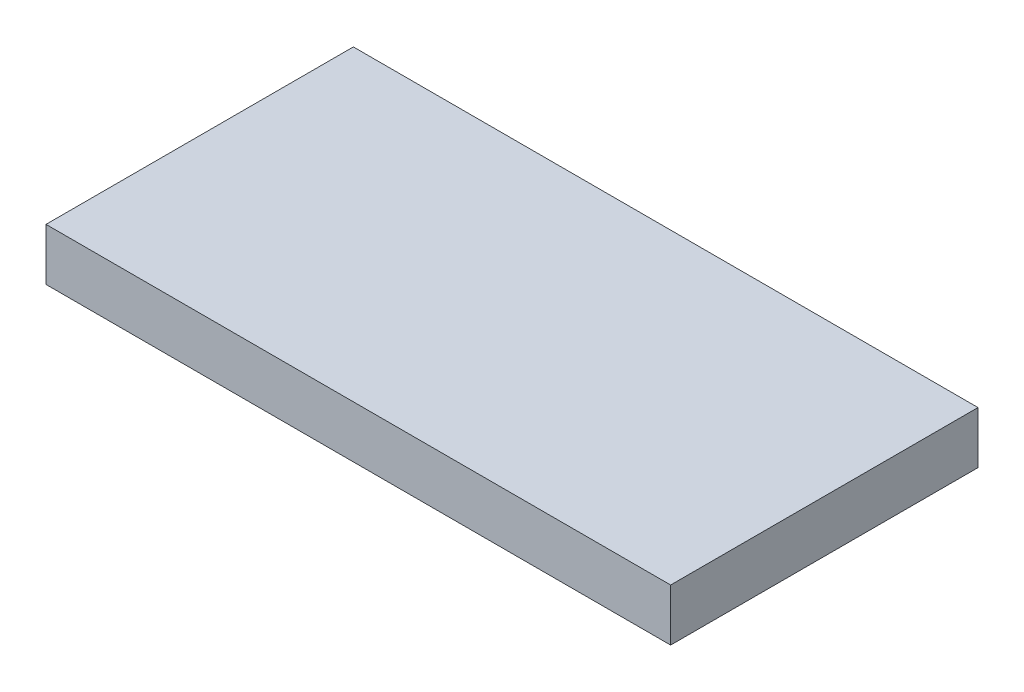
SolidWorks part; units mm, degrees
ref_plane "Front Plane" through (0, 0, 0) normal (0, 0, 1) x (1, 0, 0)
ref_plane "Top Plane" through (0, 0, 0) normal (0, 1, 0) x (1, 0, 0)
ref_plane "Right Plane" through (0, 0, 0) normal (1, 0, 0) x (0, 0, -1)
sketch "Sketch1" plane through (0, 0, 0) normal (0, 0, 1) x (1, 0, 0)
  line L0 (39, 84.25) -> (102, 84.25)
  line L1 (102, 84.25) -> (102, 89.5)
  line L2 (102, 89.5) -> (39, 89.5)
  line L3 (39, 89.5) -> (39, 84.25)
extrude "Replaceable crosshead bearing strip" add sketch "Sketch1" along normal blind 31 from offset 27
